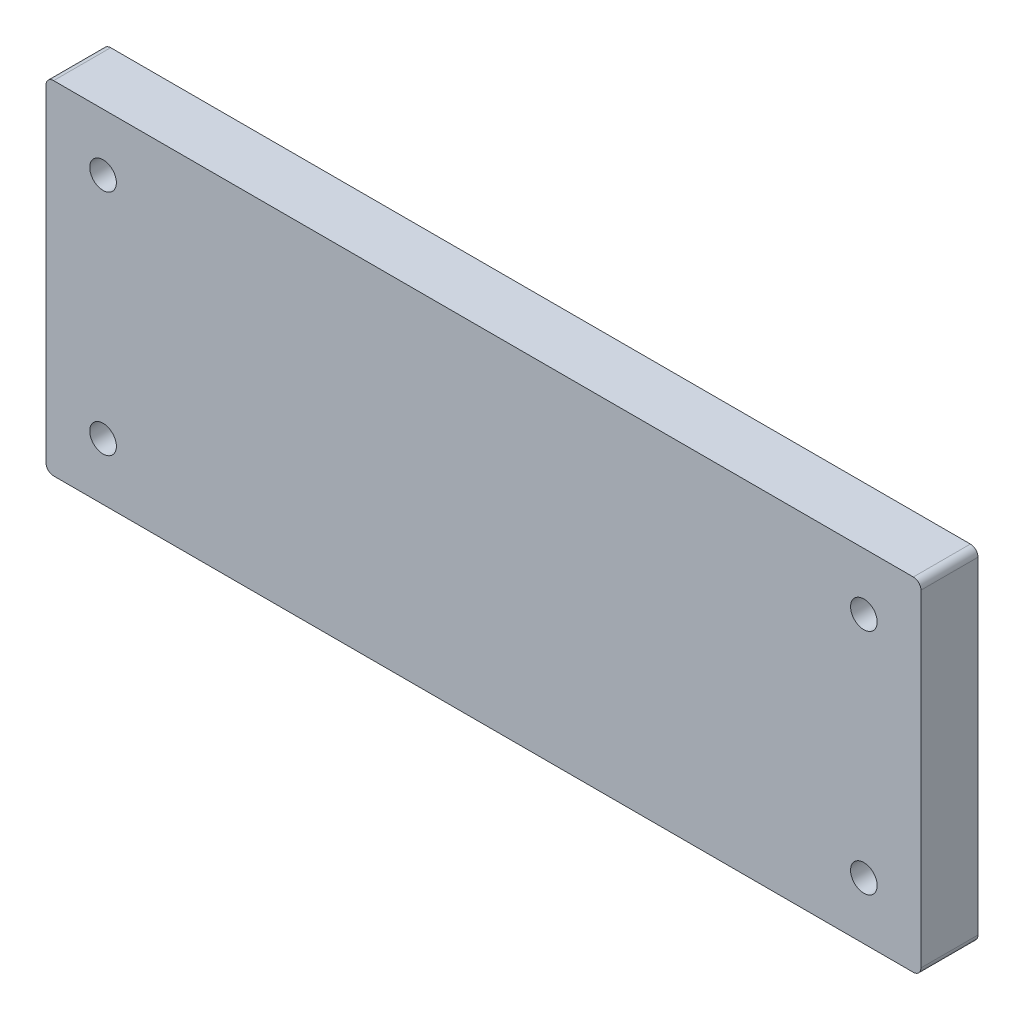
SolidWorks part; units mm, degrees
ref_plane "Vorne" through (0, 0, 0) normal (0, 0, 1) x (1, 0, 0)
ref_plane "Oben" through (0, 0, 0) normal (0, 1, 0) x (1, 0, 0)
ref_plane "Rechts" through (0, 0, 0) normal (1, 0, 0) x (0, 0, -1)
ref_plane "E_Boden" through (0, 1, 0) normal (0, 1, 0) x (1, 0, 0)
sketch "Skizze1" plane through (0, 0, 0) normal (0, 0, 1) x (1, 0, 0)
  line L0 (163.7849, 0) -> (-219.6716, 0) construction
  line L1 (0, 0) -> (0, -108.2309) construction
  line L2 (0, -108.2309) -> (0, 91.6781) construction
  line L4 (-115, 45) -> (115, 45)
  line L5 (-115, 45) -> (-115, -45)
  line L6 (-115, -45) -> (115, -45)
  line L7 (115, 45) -> (115, -45)
  dimension "D1" = 230
  dimension "90" = 90
extrude "Aufsatz-Linear austragen1" add sketch "Skizze1" along normal blind 15
hole_wizard "Ø7.0 (7) Durchmesser Bohrung1" positions "Skizze2" profile "Skizze3" hole size "Ø7.0" standard "DIN" end condition through all
sketch "Skizze2" plane through (0, 0, 15) normal (0, 0, 1) x (1, 0, 0)
  line L0 (115, -45) -> (115, 45) construction
  line L1 (-115, 45) -> (-115, -45) construction
  line L2 (115, 45) -> (-115, 45) construction
  line L3 (-115, -45) -> (115, -45) construction
  point P0 (100, -30)
  point P2 (-100, -30)
  point P4 (-100, 30)
  point P6 (100, 30)
  point P9 (0, 0)
  point P10 (0, 0)
  point P11 (0, 0)
  point P20 (0, 0)
  dimension "D1" = 15
  dimension "D2" = 15
  dimension "D3" = 15
  dimension "D4" = 15
sketch "Skizze3" plane through (100, -30, 15) normal (1, 0, 0) x (0, -1, 0)
  line L0 (0, 0) -> (0, 15)
  line L1 (0, 15) -> (3.5, 15)
  line L2 (3.5, 15) -> (3.5, 0)
  line L5 (3.5, 0) -> (0, 0)
  line L11 (0, -6.35) -> (0, 107.95) construction
  dimension "Bohrerdurchmesser" = 7
  dimension "Bohrungstiefe" = 15
fillet "Verrundung3" radius 2 2 edges at (115, 45, 7.5) (-115, 45, 7.5)
fillet "Verrundung4" radius 2 2 edges at (115, -45, 7.5) (-115, -45, 7.5)
